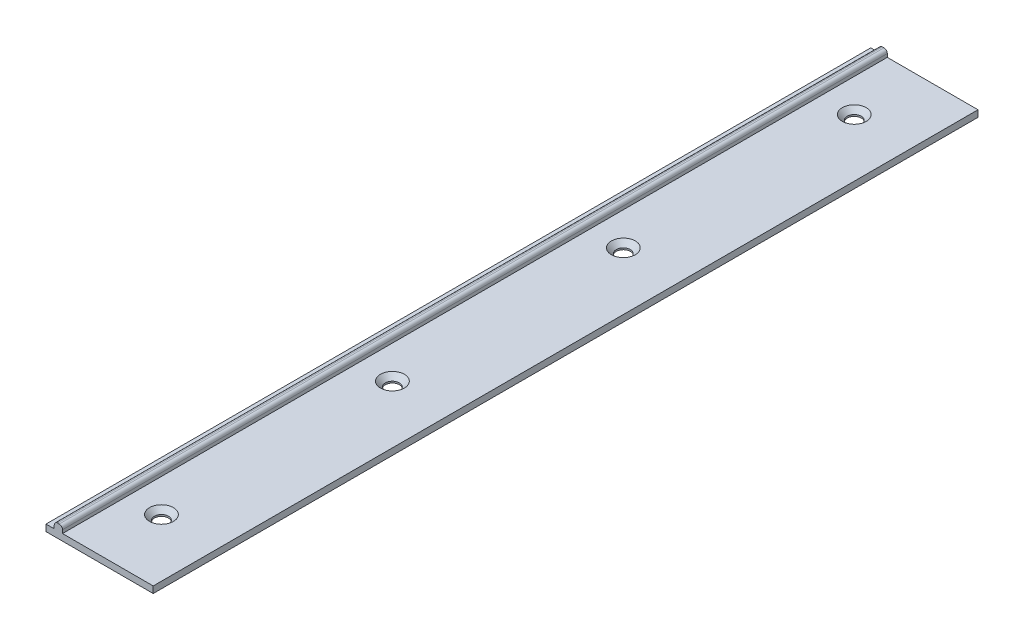
SolidWorks part; units mm, degrees
ref_plane "Ön Düzlem" through (0, 0, 0) normal (0, 0, 1) x (1, 0, 0)
ref_plane "Üst Düzlem" through (0, 0, 0) normal (0, 1, 0) x (1, 0, 0)
ref_plane "Sağ Düzlem" through (0, 0, 0) normal (1, 0, 0) x (0, 0, -1)
sketch "Çizim1" plane through (0, 0, 0) normal (0, 0, 1) x (1, 0, 0)
  line L0 (0, 0) -> (65, 0)
  line L1 (0, 0) -> (0, 4)
  line L2 (0, 4) -> (5, 4)
  line L3 (5, 4) -> (5, 8)
  line L4 (5, 8) -> (10, 8)
  line L5 (10, 8) -> (10, 4)
  line L6 (10, 4) -> (65, 4)
  line L11 (65, 4) -> (65, 0)
  dimension "D1" = 5
  dimension "D2" = 65
  dimension "D4" = 5
  dimension "D6" = 8
  dimension "D7" = 4
extrude "Yükseklik-Ekstrüzyon1" add sketch "Çizim1" against normal blind 500
fillet "Radyus1" radius 2 2 edges at (10, 8, -250) (5, 8, -250)
sketch "Çizim2" plane through (0, 0, 0) normal (0, -1, 0) x (1, 0, 0)
  line L0 (0, 0) -> (65, 0) construction
  line L1 (0, -500) -> (65, -500) construction
  line L2 (0, -500) -> (0, 0) construction
  circle A0 centre (30, -40) radius 4.25
  circle A1 centre (30, -180) radius 4.25
  circle A2 centre (30, -320) radius 4.25
  circle A3 centre (30, -460) radius 4.25
  dimension "D1" = 8.5
  dimension "D2" = 40
  dimension "D4" = 140
  dimension "D5" = 140
  dimension "D6" = 30
  dimension "D3" = 40
extrude "Kes-Ekstrüzyon1" cut sketch "Çizim2" against normal blind 10
chamfer "Pah1" distance 3 angle 45 4 edges at (30, 4, -455.75) (30, 4, -315.75) (30, 4, -175.75) (30, 4, -35.75)
